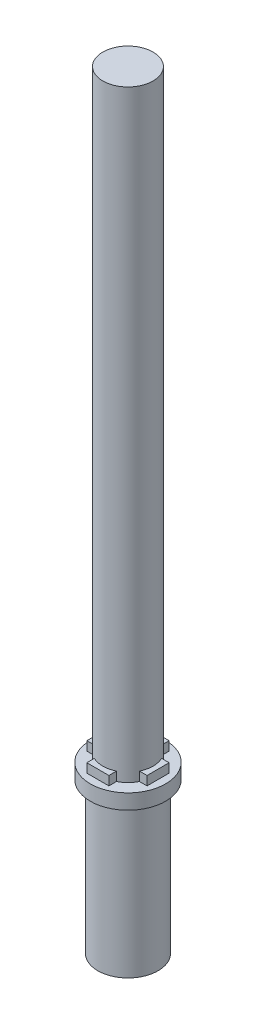
SolidWorks part; units mm, degrees
ref_plane "前视基准面" through (0, 0, 0) normal (0, 0, 1) x (1, 0, 0)
ref_plane "上视基准面" through (0, 0, 0) normal (0, 1, 0) x (1, 0, 0)
ref_plane "右视基准面" through (0, 0, 0) normal (1, 0, 0) x (0, 0, -1)
sketch "草图1" plane through (0, 0, 0) normal (0, 1, 0) x (1, 0, 0)
  circle A0 centre (0, 0) radius 5.25
  circle A1 centre (0, 0) radius 6
  dimension "D1" = 10.5
  dimension "D2" = 12
extrude "凸台-拉伸2" add sketch "草图1" along normal blind 30 contours A1 | A0
sketch "草图2" plane through (0, 30, 0) normal (0, 1, 0) x (1, 0, 0)
  circle A0 centre (0, 0) radius 7.5
  dimension "D1" = 15
extrude "凸台-拉伸3" add sketch "草图2" along normal blind 3
sketch "草图3" plane through (0, 33, 0) normal (0, 1, 0) x (1, 0, 0)
  circle A0 centre (0, 0) radius 5
  dimension "D1" = 10
extrude "凸台-拉伸4" add sketch "草图3" along normal blind 120
sketch "草图4" plane through (0, 33, 0) normal (0, 1, 0) x (1, 0, 0)
  line L0 (0, 0) -> (5, 0) construction
  line L1 (0, 0) -> (0, 5) construction
  line L3 (0, 0) -> (6, 0) construction
  line L4 (0, -2.2) -> (0, 2.2)
  line L8 (-2.2, 2.2) -> (-2.2, 6)
  line L13 (-2.2, 6) -> (2.2, 6)
  line L14 (2.2, 6) -> (2.2, 2.2)
  line L15 (2.2, 2.2) -> (6, 2.2)
  line L16 (6, 2.2) -> (6, -2.2)
  line L17 (6, -2.2) -> (2.2, -2.2)
  line L18 (2.2, -2.2) -> (2.2, -6)
  line L19 (2.2, -6) -> (-2.2, -6)
  line L20 (-2.2, -6) -> (-2.2, -2.2)
  line L21 (-2.2, -2.2) -> (-6, -2.2)
  line L22 (-6, -2.2) -> (-6, 2.2)
  line L23 (-6, 2.2) -> (-2.2, 2.2)
  point P12 (-5.6509, 2.6464)
  circle M7 centre (0, 0) radius 5
  dimension "D1" = 2.2
  dimension "D2" = 2.2
  dimension "D3" = 2.2
  dimension "D4" = 2.2
  dimension "D5" = 2.2
  dimension "D6" = 2.2
  dimension "D7" = 2.2
  dimension "D8" = 2.2
  dimension "D9" = 6
  dimension "D10" = 6
  dimension "D11" = 6
  dimension "D12" = 6
extrude "凸台-拉伸6" add sketch "草图4" along normal blind 1.8 contours L17 L16 L15 M7 | L20 L19 L18 M7 | L14 L13 L8 M7 | L23 L22 L21 M7
